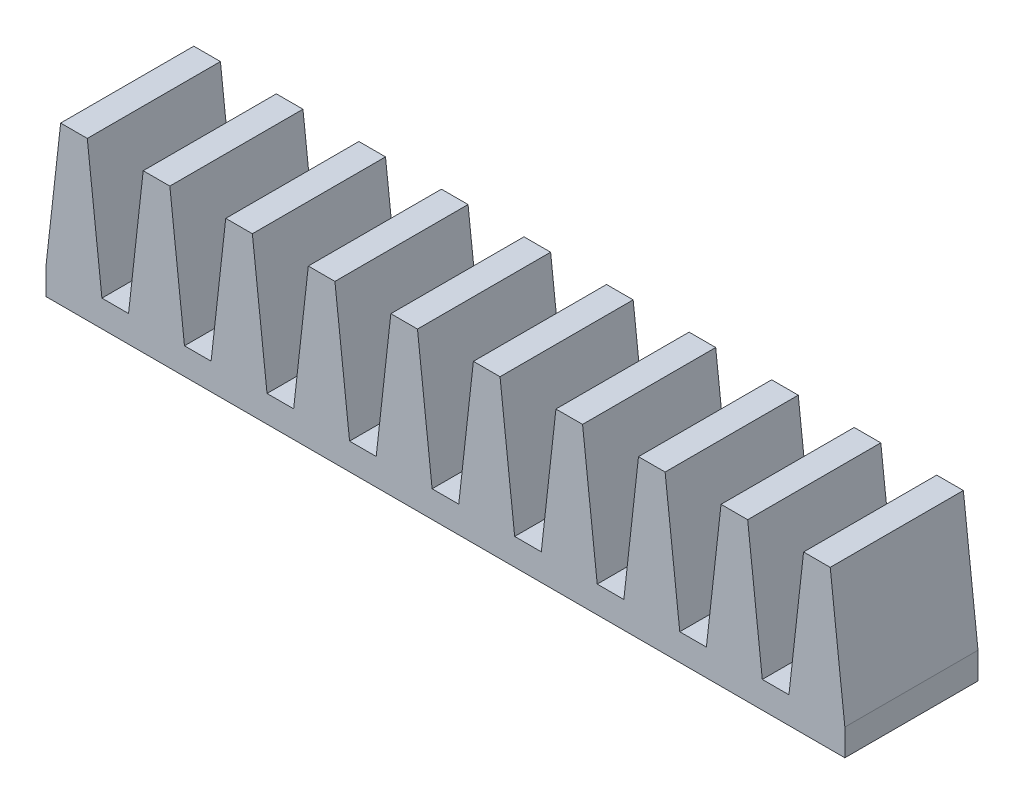
SolidWorks part; units mm, degrees
ref_plane "Front Plane" through (0, 0, 0) normal (0, 0, 1) x (1, 0, 0)
ref_plane "Top Plane" through (0, 0, 0) normal (0, 1, 0) x (1, 0, 0)
ref_plane "Right Plane" through (0, 0, 0) normal (1, 0, 0) x (0, 0, -1)
sketch "Sketch3" plane through (0, 0, 0) normal (0, 0, 1) x (1, 0, 0)
  line L1 (0, 0) -> (30, 0)
  line L2 (0, 0) -> (0, 1)
  line L3 (0, 1) -> (30, 1)
  line L4 (30, 0) -> (30, 1)
  dimension "D1" = 30
  dimension "D2" = 1
extrude "Boss-Extrude1" add sketch "Sketch3" along normal blind 5
sketch "Sketch5" plane through (0, 0, 5) normal (0, 0, 1) x (1, 0, 0)
  line L0 (0, 1) -> (0.55, 5.92)
  line L1 (0.55, 5.92) -> (1.55, 5.92)
  line L2 (1.55, 5.92) -> (2.1, 1)
  line L3 (30, 1) -> (0, 1) construction
  line L4 (2.1, 1) -> (0, 1)
  line L9 (0.275, 3.46) -> (8.8176, 3.46) construction
  point P18 (0, 0)
  point P19 (0, 0)
  point P20 (0, 0)
  dimension "D1" = 1
  dimension "D2" = 2.1
extrude "Boss-Extrude2" add sketch "Sketch5" against normal blind 5
pattern_linear "LPattern1" count 10 spacing 3.1 along (1, 0, 0) of "Boss-Extrude2"
